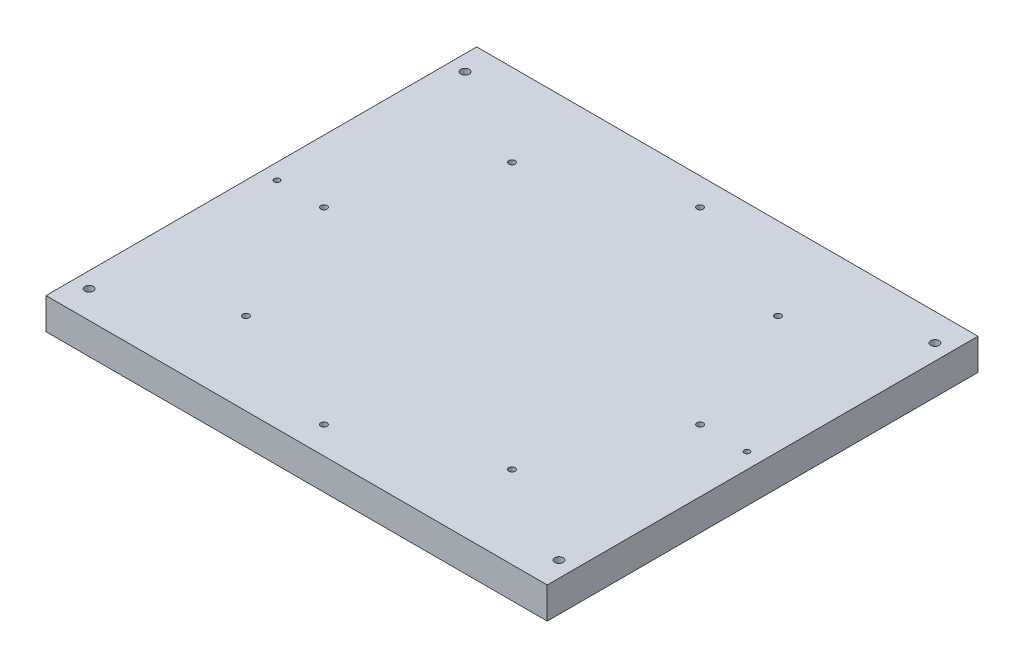
SolidWorks part; units mm, degrees
material "6061 Alloy"
ref_plane "Front Plane" through (0, 0, 0) normal (0, 0, 1) x (1, 0, 0)
ref_plane "Top Plane" through (0, 0, 0) normal (0, 1, 0) x (1, 0, 0)
ref_plane "Right Plane" through (0, 0, 0) normal (1, 0, 0) x (0, 0, -1)
sketch "Sketch1" plane through (0, 0, 0) normal (0, 1, 0) x (1, 0, 0)
  line L1 (-201.6125, -173.0375) -> (204.7875, -173.0375)
  line L2 (-201.6125, -173.0375) -> (-201.6125, 176.2125)
  line L3 (-201.6125, 176.2125) -> (204.7875, 176.2125)
  line L4 (204.7875, -173.0375) -> (204.7875, 176.2125)
  line L5 (-201.6125, -173.0375) -> (204.7875, 176.2125) construction
  line L6 (-201.6125, 176.2125) -> (204.7875, -173.0375) construction
  dimension "D2" = 406.4
  dimension "D3" = 349.25
extrude "Boss-Extrude1" add sketch "Sketch1" along normal blind 25.4
sketch "Sketch2" plane through (0, 25.4, 0) normal (0, 1, 0) x (1, 0, 0)
  line L1 (106.1984, -109.3971) -> (-106.1984, -109.3971) construction
  line L2 (152.4658, 0) -> (62.909, 42.9989) construction
  line L3 (62.909, 42.9989) -> (5.7836, -75.9802) construction
  line L4 (0, 0) -> (62.909, 42.9989) construction
  line L5 (0, 0) -> (-80.1414, 38.4782) construction
  line L6 (0, 0) -> (5.7836, -75.9802) construction
  line L7 (5.7836, -75.9802) -> (9.0752, -119.2224) construction
  line L8 (62.909, 42.9989) -> (79.8681, 54.5906) construction
  line L9 (152.4658, 0) -> (190.5, 0) construction
  line L11 (-80.1414, 38.4782) -> (0, 0)
  line L12 (79.8681, 54.5906) -> (0, 0)
  line L13 (9.0752, -119.2224) -> (0, 0)
  line L14 (62.909, 42.9989) -> (5.7836, -75.9802)
  line L15 (-152.4658, 0) -> (152.4658, 0) construction
  line L16 (1.5875, -173.0375) -> (1.5875, 176.2125) construction
  line L17 (-201.6125, -173.0375) -> (204.7875, -173.0375) construction
  line L18 (204.7875, 176.2125) -> (-201.6125, 176.2125) construction
  line L19 (-152.4658, 0) -> (-190.5, 0) construction
  line L21 (204.7875, 1.5875) -> (204.7875, 109.3971) construction
  line L22 (204.7875, -173.0375) -> (204.7875, 176.2125) construction
  line L23 (106.1984, 109.3971) -> (-106.1984, 109.3971) construction
  arc A0 (-68.6926, 32.9813) -> (5.7836, -75.9802) centre (0, 0) ccw
  arc A1 (-80.1414, 38.4782) -> (6.7476, -88.6436) centre (0, 0) ccw
  circle A2 centre (0, 0) radius 152.4658
  circle A3 centre (0, 0) radius 190.5
  arc A5 (88.9, 0) -> (73.3938, 50.1653) centre (0, 0) ccw
  arc A6 (76.2, 0) -> (62.909, 42.9989) centre (0, 0) ccw
  dimension "D1" = 120
  dimension "D3" = 381
  dimension "D2" = 120
  dimension "D5" = 107.8096
sketch "Sketch7" plane through (0, 25.4, 0) normal (0, 1, 0) x (1, 0, 0)
  line L0 (-201.6125, 1.5875) -> (204.7875, 1.5875) construction
  line L1 (-201.6125, 176.2125) -> (-201.6125, -173.0375) construction
  line L2 (204.7875, -173.0375) -> (204.7875, 176.2125) construction
  line L3 (1.5875, -150.8125) -> (1.5875, 153.9875) construction
  line L6 (204.7875, 153.9875) -> (192.0875, 153.9875) construction
  line L7 (204.7875, -150.8125) -> (192.0875, -150.8125) construction
  line L8 (-201.6125, -150.8125) -> (-188.9125, -150.8125) construction
  line L9 (-201.6125, 153.9875) -> (-188.9125, 153.9875) construction
  point P9 (1.5875, 1.5875)
  dimension "D1" = 152.4
  dimension "D2" = 381
hole_wizard "1/4 Clearance Hole1" positions "3DSketch7" profile "Sketch15" hole size "1/4" standard "Ansi Inch"
sketch3d "3DSketch7"
  point P0 (-188.9125, 25.4, -153.9875)
  point P3 (192.0875, 25.4, -153.9875)
  point P6 (192.0875, 25.4, 150.8125)
  point P9 (-188.9125, 25.4, 150.8125)
sketch "Sketch15" plane through (-188.9125, 25.4, -153.9875) normal (1, 0, 0) x (0, 0, 1)
  line L0 (0, 0) -> (0, 72.0298)
  line L1 (0, 72.0298) -> (3.3782, 70)
  line L2 (3.3782, 70) -> (3.3782, 0)
  line L5 (3.3782, 0) -> (0, 0)
  line L10 (0, 72.0298) -> (-3.3782, 70) construction
  line L11 (0, -6.35) -> (0, 107.95) construction
  dimension "Hole Dia." = 6.7564
  dimension "Hole Depth" = 70
  dimension "Drill Angle" = 118
sketch "Sketch16" plane through (0, 25.4, 0) normal (0, 1, 0) x (1, 0, 0)
  line L0 (-201.6125, 176.2125) -> (204.7875, 176.2125) construction
  line L1 (1.5875, 176.2125) -> (1.5875, -173.0375) construction
  line L2 (-201.6125, -173.0375) -> (204.7875, -173.0375) construction
  line L3 (1.5875, 1.5875) -> (192.0875, 1.5875) construction
  line L4 (1.5875, 1.5875) -> (-188.9125, 1.5875) construction
  dimension "D1" = 190.5
  dimension "D2" = 190.5
hole_wizard "#8 Clearance Hole1" positions "3DSketch8" profile "Sketch17" hole size "#8" standard "Ansi Inch"
sketch3d "3DSketch8"
  point P0 (-188.9125, 25.4, -1.5875)
  point P3 (192.0875, 25.4, -1.5875)
sketch "Sketch17" plane through (-188.9125, 25.4, -1.5875) normal (1, 0, 0) x (0, 0, 1)
  line L0 (0, 0) -> (0, 71.3507)
  line L1 (0, 71.3507) -> (2.2479, 70)
  line L2 (2.2479, 70) -> (2.2479, 0)
  line L5 (2.2479, 0) -> (0, 0)
  line L10 (0, 71.3507) -> (-2.2479, 70) construction
  line L11 (0, -6.35) -> (0, 107.95) construction
  dimension "Hole Dia." = 4.4958
  dimension "Hole Depth" = 70
  dimension "Drill Angle" = 118
sketch "Sketch18" plane through (0, 25.4, 0) normal (0, 1, 0) x (1, 0, 0)
  line L0 (1.5875, 176.2125) -> (1.5875, -173.0375) construction
  line L1 (-106.2355, -106.2355) -> (109.4105, -106.2355)
  line L2 (-106.2355, -106.2355) -> (-106.2355, 109.4105)
  line L3 (-106.2355, 109.4105) -> (109.4105, 109.4105)
  line L4 (109.4105, -106.2355) -> (109.4105, 109.4105)
  line L5 (-106.2355, -106.2355) -> (109.4105, 109.4105) construction
  line L6 (-106.2355, 109.4105) -> (109.4105, -106.2355) construction
  line L7 (1.5875, 154.0722) -> (-150.8972, 1.5875)
  line L8 (1.5875, 1.5875) -> (-188.9125, 1.5875) construction
  line L9 (1.5875, 154.0722) -> (1.5875, 1.5875)
  line L10 (1.5875, 1.5875) -> (-150.8972, 1.5875)
  line L11 (154.0722, 1.5875) -> (1.5875, -150.8972)
  line L12 (1.5875, 1.5875) -> (1.5875, -150.8972)
  line L13 (154.0722, 1.5875) -> (1.5875, 1.5875)
  point P0 (1.5875, 1.5875)
  dimension "D1" = 215.646
  dimension "D2" = 215.646
  dimension "D3" = 215.646
hole_wizard "1/4-20 Tapped Hole1" positions "3DSketch9" profile "Sketch19" tap size "1/4-20" standard "Ansi Inch"
sketch3d "3DSketch9"
  point P0 (1.5875, 25.4, -154.0722)
  point P3 (-106.2355, 25.4, -109.4105)
  point P6 (109.4105, 25.4, -109.4105)
  point P9 (154.0722, 25.4, -1.5875)
  point P12 (-150.8972, 25.4, -1.5875)
  point P15 (-106.2355, 25.4, 106.2355)
  point P18 (1.5875, 25.4, 150.8972)
  point P21 (109.4105, 25.4, 106.2355)
sketch "Sketch19" plane through (1.5875, 25.4, -154.0722) normal (1, 0, 0) x (0, 0, 1)
  line L0 (0, 0) -> (0, 40.5838)
  line L1 (0, 40.5838) -> (2.5527, 39.05)
  line L2 (2.5527, 39.05) -> (2.5527, 0)
  line L5 (2.5527, 0) -> (0, 0)
  line L10 (0, 40.5838) -> (-2.5527, 39.05) construction
  line L11 (0, -6.35) -> (0, 107.95) construction
  dimension "Tap Drill Dia." = 5.1054
  dimension "Tap Drill Depth" = 39.05
  dimension "Drill Angle" = 118
cosmetic thread "Hole Thread1" parameters "D1"=12.7, "D2"=6.35
cosmetic thread "Hole Thread2" parameters "D1"=12.7, "D2"=6.35
cosmetic thread "Hole Thread3" parameters "D1"=12.7, "D2"=6.35
cosmetic thread "Hole Thread4" parameters "D1"=12.7, "D2"=6.35
cosmetic thread "Hole Thread5" parameters "D1"=12.7, "D2"=6.35
cosmetic thread "Hole Thread6" parameters "D1"=12.7, "D2"=6.35
cosmetic thread "Hole Thread7" parameters "D1"=12.7, "D2"=6.35
cosmetic thread "Hole Thread8" parameters "D1"=12.7, "D2"=6.35
